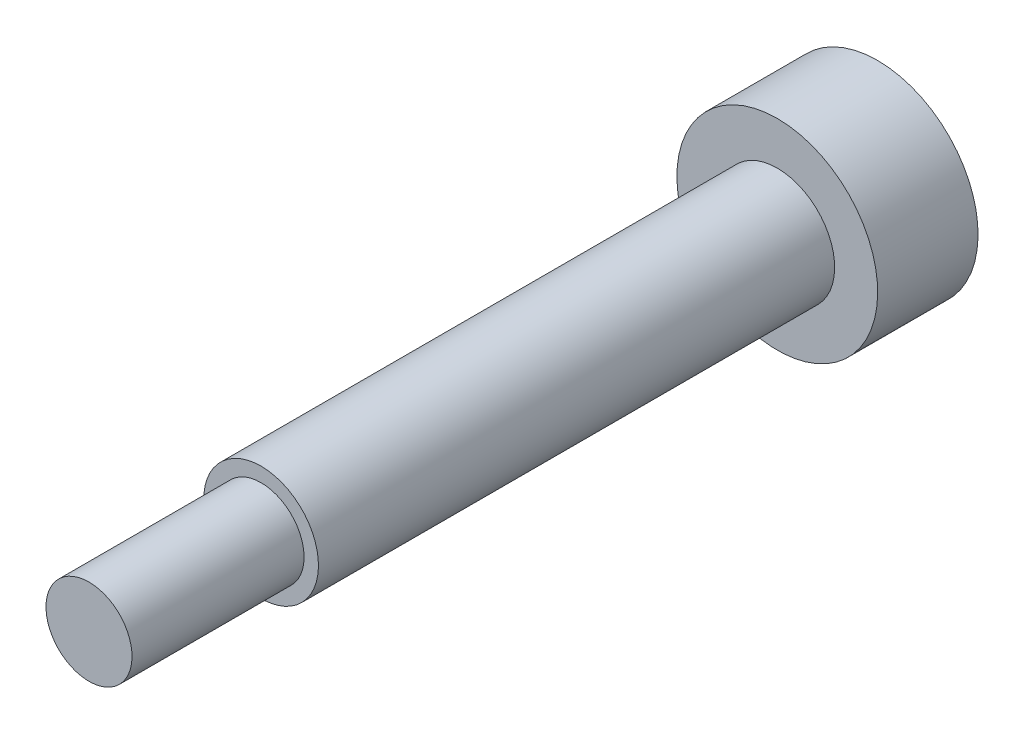
SolidWorks part; units mm, degrees
ref_plane "前视基准面" through (0, 0, 0) normal (0, 0, 1) x (1, 0, 0)
ref_plane "上视基准面" through (0, 0, 0) normal (0, 1, 0) x (1, 0, 0)
ref_plane "右视基准面" through (0, 0, 0) normal (1, 0, 0) x (0, 0, -1)
other "Configuration Table"
sketch "草图1" plane through (0, 0, 0) normal (1, 0, 0) x (0, 0, -1)
  line L13 (0, 0) -> (0, 1.5)
  line L14 (0, 1.5) -> (6, 1.5)
  line L15 (6, 1.5) -> (6, 2)
  line L16 (6, 2) -> (24, 2)
  line L17 (24, 2) -> (24, 3.5)
  line L18 (24, 3.5) -> (27.5, 3.5)
  line L19 (27.5, 3.5) -> (27.5, 0)
  line L20 (27.5, 0) -> (0, 0)
  line L21 (0, 0) -> (0, -1.5) construction
  line L22 (24, -2) -> (24, -3.5) construction
  line L23 (24, -3.5) -> (27.5, -3.5) construction
  line L24 (6, -2) -> (24, -2) construction
  line L25 (6, -1.5) -> (6, -2) construction
  line L26 (0, -1.5) -> (6, -1.5) construction
  line L27 (27.5, 0) -> (27.5, -3.5) construction
  dimension "D1" = 3
  dimension "D2" = 4
  dimension "D3" = 6
  dimension "D4" = 3.5
  dimension "D5" = 7
  dimension "D6" = 18
revolve "旋转2" add sketch "草图1" angle 360 about L20
